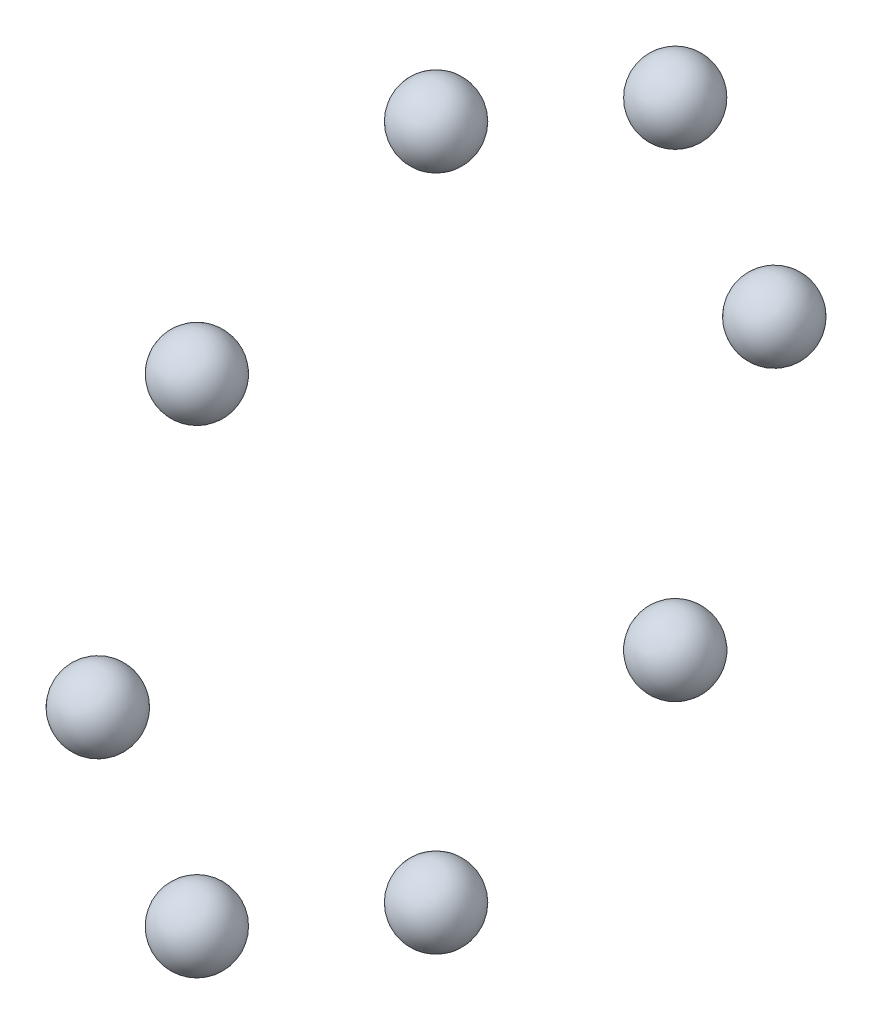
SolidWorks part; units mm, degrees
ref_plane "Front Plane" through (0, 0, 0) normal (0, 0, 1) x (1, 0, 0)
ref_plane "Top Plane" through (0, 0, 0) normal (0, 1, 0) x (1, 0, 0)
ref_plane "Right Plane" through (0, 0, 0) normal (1, 0, 0) x (0, 0, -1)
sketch "Sketch1" plane through (0, 0, 0) normal (0, 0, 1) x (1, 0, 0)
  line L0 (0, 48.6773) -> (0, 60.4827)
  arc A0 (0, 60.4827) -> (0, 48.6773) centre (0, 54.58) ccw
  dimension "D1" = 54.58
revolve "Revolve1" add sketch "Sketch1" angle 360 about L0
sketch "Sketch2" plane through (0, 0, 0) normal (0, 0, 1) x (1, 0, 0)
  line L0 (-1000, 0) -> (49000, 0) construction
pattern_circular "CirPattern1" count 8 over 360 about axis through (0, 0, 0) along (1, 0, 0) of bodies 101
